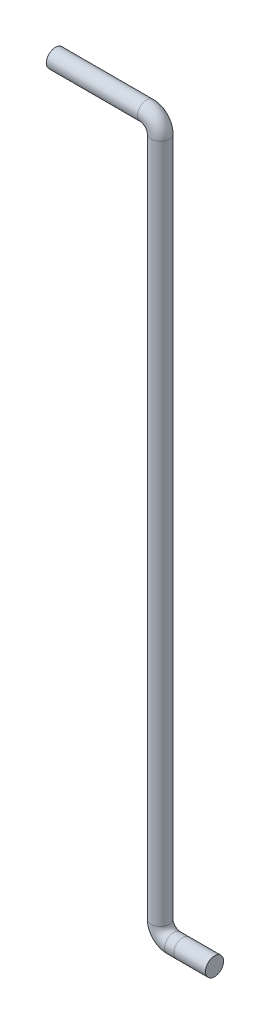
SolidWorks part; units mm, degrees
ref_plane "Front Plane" through (0, 0, 0) normal (0, 0, 1) x (1, 0, 0)
ref_plane "Top Plane" through (0, 0, 0) normal (0, 1, 0) x (1, 0, 0)
ref_plane "Right Plane" through (0, 0, 0) normal (1, 0, 0) x (0, 0, -1)
sketch "Sketch1" plane through (0, 0, 0) normal (0, 0, 1) x (1, 0, 0)
  line L0 (-17.55, 78) -> (-7.5, 78)
  line L1 (-6, 76.5) -> (-6, 1.5)
  line L2 (-4.5, 0) -> (-3.5, 0)
  line L3 (-3.5, 0) -> (0, 0)
  arc A0 (-6, 76.5) -> (-7.5, 78) centre (-7.5, 76.5) ccw
  arc A1 (-6, 1.5) -> (-4.5, 0) centre (-4.5, 1.5) ccw
  dimension "D2" = 1.5
  dimension "D1" = 1.5
  dimension "D3" = 14.05
  dimension "D4" = 1
  dimension "D5" = 78
  dimension "D6" = 3.5
sketch "Sketch2" plane through (0, 0, 0) normal (1, 0, 0) x (0, 0, -1)
  circle A0 centre (0, 0) radius 1
  dimension "D1" = 2
sweep "Sweep1" add profiles "Sketch2" path "Sketch1"
